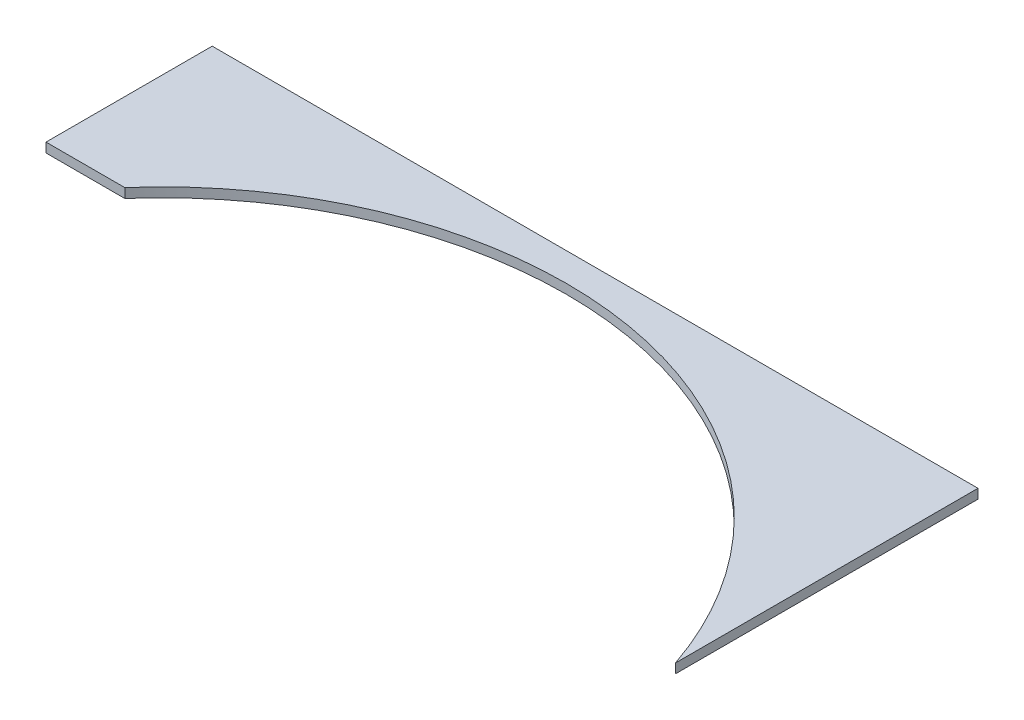
SolidWorks part; units mm, degrees
material "Acrylic (Medium-high impact)"
ref_plane "Front Plane" through (0, 0, 0) normal (0, 0, 1) x (1, 0, 0)
ref_plane "Top Plane" through (0, 0, 0) normal (0, 1, 0) x (1, 0, 0)
ref_plane "Right Plane" through (0, 0, 0) normal (1, 0, 0) x (0, 0, -1)
sketch "Sketch1" plane through (0, 0, 0) normal (0, 1, 0) x (1, 0, 0)
  line L6 (-257.175, 0) -> (-257.175, -203.2)
  line L11 (-257.175, 0) -> (257.175, 0)
  line L13 (257.175, 0) -> (257.175, -203.2)
  line L14 (0, -19.05) -> (0, 0) construction
  line L15 (0, -19.05) -> (257.175, -19.05) construction
  arc A3 (257.175, -203.2) -> (0, -19.05) centre (0, -290.7041) ccw
  arc A4 (0, -19.05) -> (-257.175, -203.2) centre (0, -290.7041) ccw
  point P2 (0, 0)
  dimension "D1" = 514.35
  dimension "D2" = 19.05
  dimension "D3" = 203.2
extrude "Boss-Extrude1" add sketch "Sketch1" along normal blind 6.35
sketch "Sketch2" plane through (0, 6.35, 0) normal (0, 1, 0) x (1, 0, 0)
  line L0 (-257.175, -111.6203) -> (-204.2668, -111.6203)
  line L3 (257.175, -203.2) -> (257.175, 0)
  line L4 (257.175, 0) -> (-257.175, 0)
  line L5 (-257.175, 0) -> (-257.175, -203.2)
  line L8 (-257.175, -111.6203) -> (-257.175, -203.2)
  arc A1 (257.175, -203.2) -> (-257.175, -203.2) centre (0, -290.7041) ccw
  arc A2 (-204.2668, -111.6203) -> (-257.175, -203.2) centre (0, -290.7041) ccw
  dimension "D2" = 91.5797
  dimension "D1" = 0
extrude "Cut-Extrude1" cut sketch "Sketch2" against normal through all
